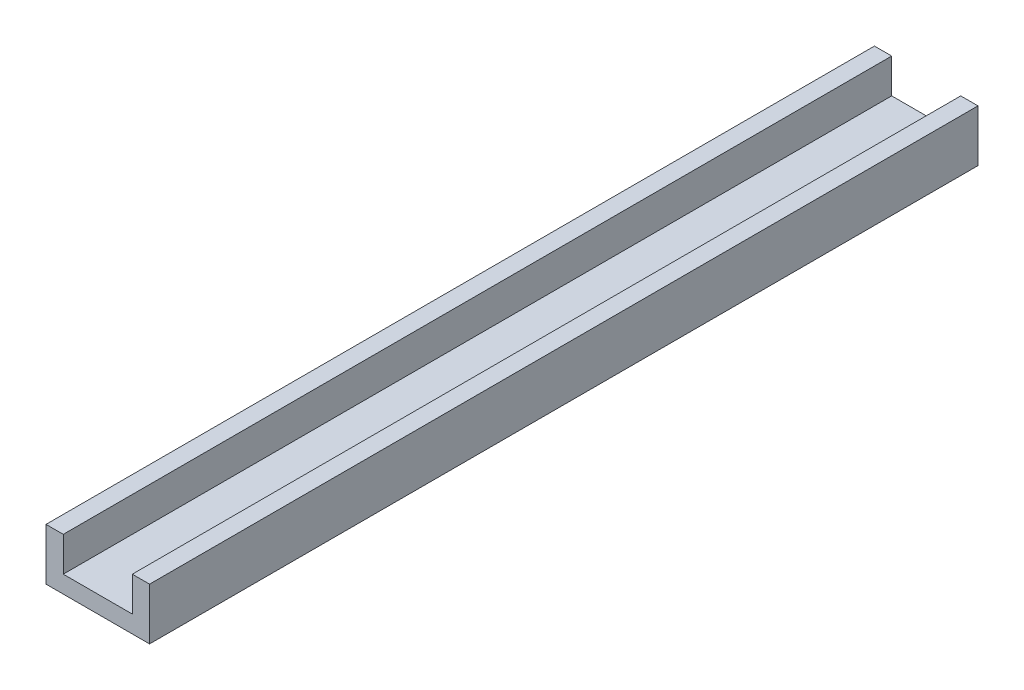
SolidWorks part; units mm, degrees
ref_plane "Front Plane" through (0, 0, 0) normal (0, 0, 1) x (1, 0, 0)
ref_plane "Top Plane" through (0, 0, 0) normal (0, 1, 0) x (1, 0, 0)
ref_plane "Right Plane" through (0, 0, 0) normal (1, 0, 0) x (0, 0, -1)
sketch "Sketch1" plane through (0, 0, 0) normal (0, 0, 1) x (1, 0, 0)
  line L1 (0, 0) -> (38.1, 0)
  line L2 (0, 0) -> (0, 19.05)
  line L3 (0, 19.05) -> (38.1, 19.05)
  line L4 (38.1, 0) -> (38.1, 19.05)
  dimension "D1" = 38.1
  dimension "D2" = 19.05
extrude "Boss-Extrude1" add sketch "Sketch1" along normal blind 304.8
sketch "Sketch2" plane through (0, 0, 304.8) normal (0, 0, 1) x (1, 0, 0)
  line L0 (38.1, 19.05) -> (0, 19.05) construction
  line L1 (6.35, 19.05) -> (31.75, 19.05)
  line L2 (6.35, 19.05) -> (6.35, 6.35)
  line L3 (6.35, 6.35) -> (31.75, 6.35)
  line L4 (31.75, 19.05) -> (31.75, 6.35)
  line L5 (0, 19.05) -> (0, 0) construction
  line L6 (38.1, 0) -> (38.1, 19.05) construction
  line L7 (0, 0) -> (38.1, 0) construction
  dimension "D1" = 6.35
  dimension "D2" = 6.35
  dimension "D3" = 6.35
extrude "Cut-Extrude1" cut sketch "Sketch2" against normal up to next
sketch "Sketch3" plane through (0, 6.35, 0) normal (0, 1, 0) x (1, 0, 0)
  line L0 (6.35, 0) -> (6.35, -304.8) construction
  line L1 (6.35, -25.4) -> (31.75, -25.4)
  line L2 (6.35, -25.4) -> (6.35, -31.75)
  line L3 (6.35, -31.75) -> (31.75, -31.75)
  line L4 (31.75, -25.4) -> (31.75, -31.75)
  line L5 (31.75, 0) -> (31.75, -304.8) construction
  line L6 (6.35, 0) -> (31.75, 0) construction
  dimension "D1" = 6.35
  dimension "D2" = 25.4
extrude "Boss-Extrude2" [suppressed] add sketch "Sketch3" along normal up to surface (12.7 mm away)
